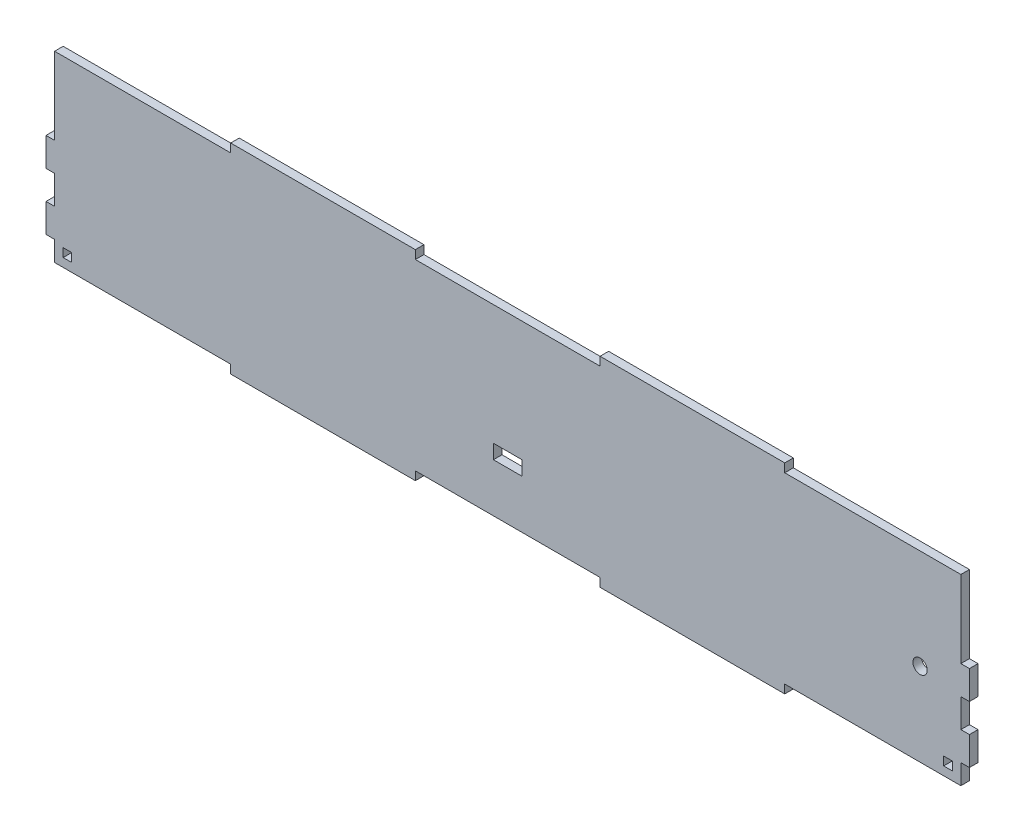
SolidWorks part; units mm, degrees
ref_plane "Front Plane" through (0, 0, 0) normal (0, 0, 1) x (1, 0, 0)
ref_plane "Top Plane" through (0, 0, 0) normal (0, 1, 0) x (1, 0, 0)
ref_plane "Right Plane" through (0, 0, 0) normal (1, 0, 0) x (0, 0, -1)
sketch "Sketch1" plane through (0, 0, 0) normal (0, 0, 1) x (1, 0, 0)
  line L0 (0, 39.5853) -> (0, 29.5853)
  line L1 (320, 66.5853) -> (320, 39.5853)
  line L2 (0, 39.5853) -> (3, 39.5853)
  line L3 (320, 39.5853) -> (323, 39.5853)
  line L4 (0, 29.5853) -> (3, 29.5853)
  line L5 (3, 39.5853) -> (3, 66.5853)
  line L6 (323, 39.5853) -> (323, 29.5853)
  line L7 (3, 29.5853) -> (3, 19.5853)
  line L8 (3, 19.5853) -> (0, 19.5853)
  line L9 (0, 19.5853) -> (0, 9.5853)
  line L10 (0, 9.5853) -> (3, 9.5853)
  line L11 (3, 9.5853) -> (3, 2.5853)
  line L12 (323, 29.5853) -> (320, 29.5853)
  line L13 (320, 29.5853) -> (320, 19.5853)
  line L14 (320, 19.5853) -> (323, 19.5853)
  line L15 (323, 19.5853) -> (323, 9.5853)
  line L16 (323, 9.5853) -> (320, 9.5853)
  line L17 (320, 9.5853) -> (320, 2.5853)
  line L18 (3, 66.5853) -> (64.6, 66.5853)
  line L19 (3, 2.5853) -> (64.6, 2.5853)
  line L20 (64.6, 66.5853) -> (64.6, 69.5853)
  line L21 (64.6, 69.5853) -> (129.2, 69.5853)
  line L22 (129.2, 69.5853) -> (129.2, 66.5853)
  line L23 (129.2, 66.5853) -> (193.8, 66.5853)
  line L24 (193.8, 66.5853) -> (193.8, 69.5853)
  line L25 (193.8, 69.5853) -> (258.4, 69.5853)
  line L26 (258.4, 69.5853) -> (258.4, 66.5853)
  line L27 (258.4, 66.5853) -> (320, 66.5853)
  line L28 (64.6, 2.5853) -> (64.6, -0.4147)
  line L29 (64.6, -0.4147) -> (129.2, -0.4147)
  line L30 (129.2, -0.4147) -> (129.2, 2.5853)
  line L31 (129.2, 2.5853) -> (193.8, 2.5853)
  line L32 (193.8, 2.5853) -> (193.8, -0.4147)
  line L33 (193.8, -0.4147) -> (258.4, -0.4147)
  line L34 (258.4, -0.4147) -> (258.4, 2.5853)
  line L35 (258.4, 2.5853) -> (320, 2.5853)
  line L36 (317, 5.5853) -> (317, 8.5853)
  line L37 (6, 5.5853) -> (9, 5.5853)
  line L38 (6, 5.5853) -> (6, 8.5853)
  line L39 (6, 8.5853) -> (9, 8.5853)
  line L40 (9, 5.5853) -> (9, 8.5853)
  line L41 (314, 8.5853) -> (317, 8.5853)
  line L42 (314, 5.5853) -> (314, 8.5853)
  line L43 (314, 5.5853) -> (317, 5.5853)
  line L45 (156.5, 19.5853) -> (166.5, 19.5853)
  line L46 (156.5, 19.5853) -> (156.5, 24.5853)
  line L47 (156.5, 24.5853) -> (166.5, 24.5853)
  line L48 (166.5, 19.5853) -> (166.5, 24.5853)
  circle A0 centre (305.7332, 31.6623) radius 2.5
  point P51 (0, 0)
  dimension "D23" = 5
  dimension "D1" = 27
  dimension "D2" = 3
  dimension "D3" = 10
  dimension "D4" = 10
  dimension "D5" = 10
  dimension "D6" = 7
  dimension "D7" = 3
  dimension "D8" = 317
  dimension "D9" = 317
  dimension "D10" = 7
  dimension "D11" = 3
  dimension "D12" = 61.6
  dimension "D13" = 61.6
  dimension "D14" = 64.6
  dimension "D15" = 64.6
  dimension "D16" = 3
  dimension "D17" = 3
  dimension "D18" = 3
  dimension "D19" = 3
  dimension "D20" = 6
  dimension "D22" = 27
  dimension "D25" = 156.5
  dimension "D21" = 2
extrude "Boss-Extrude1" add sketch "Sketch1" along normal blind 3
